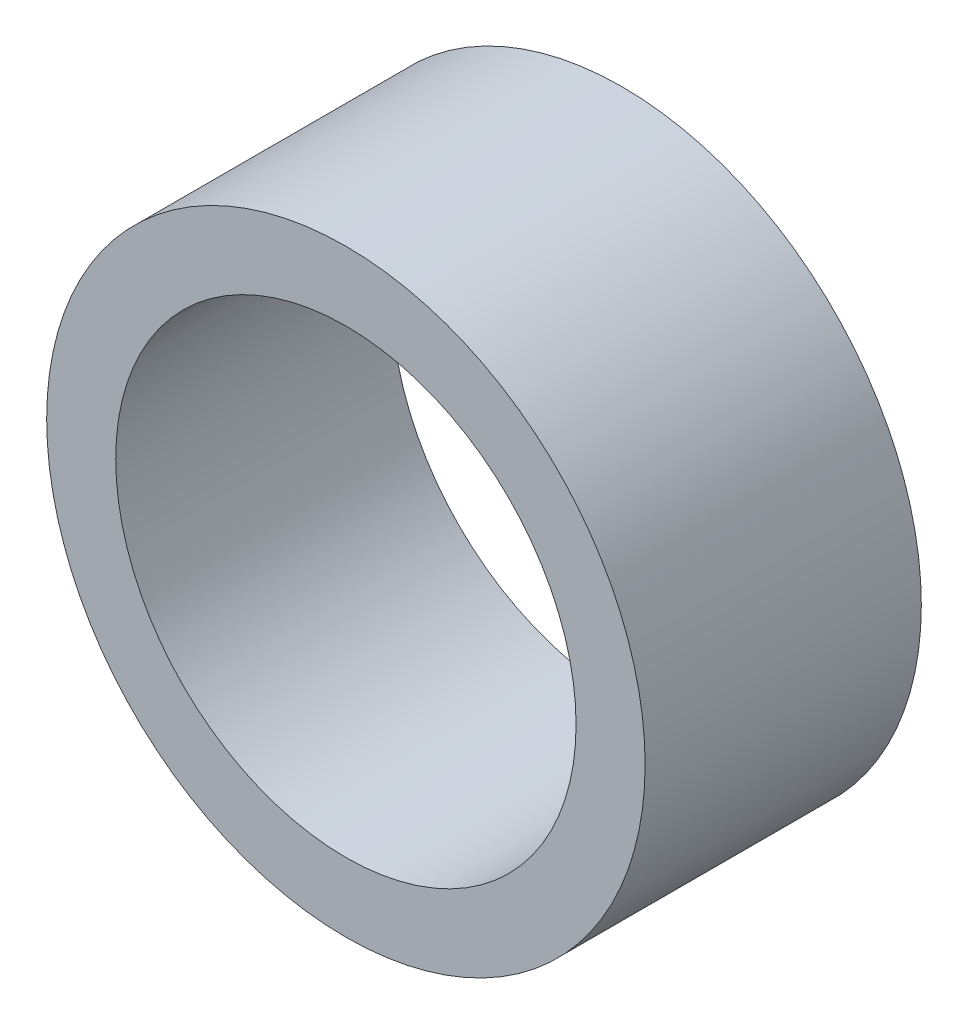
SolidWorks part; units mm, degrees
ref_plane "Front Plane" through (0, 0, 0) normal (0, 0, 1) x (1, 0, 0)
ref_plane "Top Plane" through (0, 0, 0) normal (0, 1, 0) x (1, 0, 0)
ref_plane "Right Plane" through (0, 0, 0) normal (1, 0, 0) x (0, 0, -1)
sketch "Sketch1" plane through (0, 0, 0) normal (0, 0, 1) x (1, 0, 0)
  circle A0 centre (0, 0) radius 5
  circle A1 centre (0, 0) radius 6.5
  dimension "D1" = 10
  dimension "D2" = 13
extrude "Boss-Extrude1" add sketch "Sketch1" along normal blind 6
